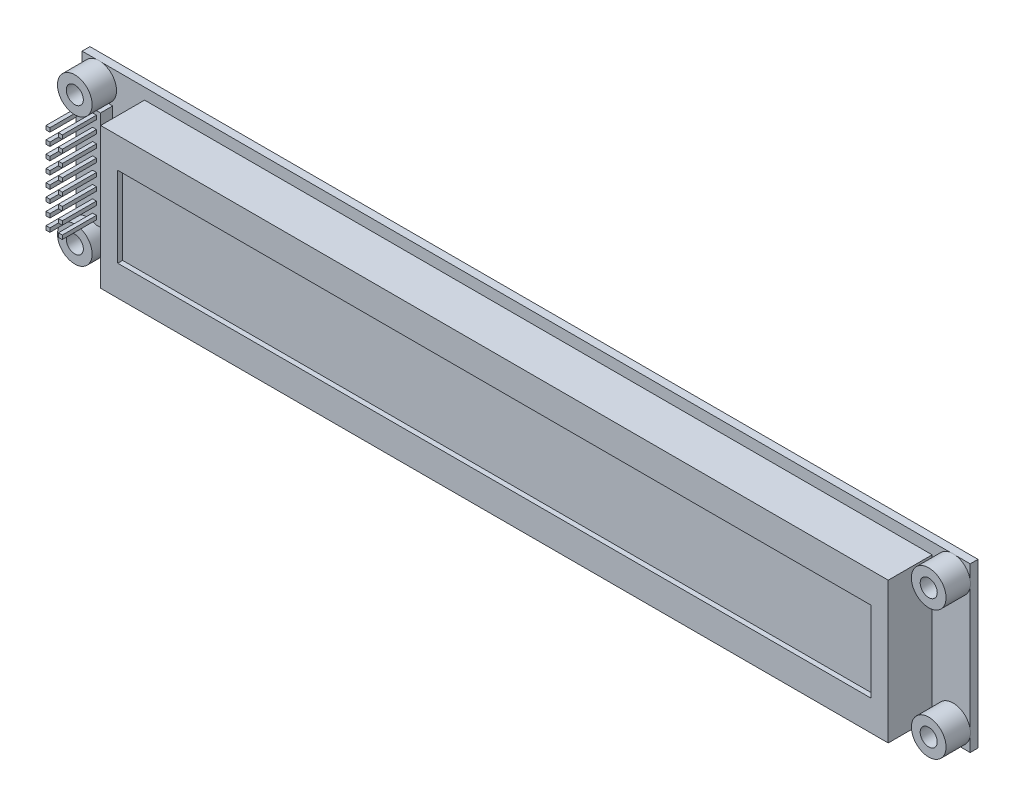
SolidWorks part; units mm, degrees
ref_plane "Спереди" through (0, 0, 0) normal (0, 0, 1) x (1, 0, 0)
ref_plane "Сверху" through (0, 0, 0) normal (0, 1, 0) x (1, 0, 0)
ref_plane "Справа" through (0, 0, 0) normal (1, 0, 0) x (0, 0, -1)
ref_plane "Плоскость4" through (0, 0, -6.6) normal (0, 0, 1) x (1, 0, 0)
sketch "Эскиз2" plane through (0, 0, -6.6) normal (0, 0, 1) x (1, 0, 0)
  line L1 (-91, -16.75) -> (91, -16.75)
  line L2 (-91, -16.75) -> (-91, 16.75)
  line L3 (-91, 16.75) -> (91, 16.75)
  line L4 (91, -16.75) -> (91, 16.75)
  line L5 (-91, -16.75) -> (91, 16.75) construction
  line L6 (-91, 16.75) -> (91, -16.75) construction
  point P0 (0, 0)
  dimension "D1" = 182
  dimension "D2" = 33.5
extrude "Бобышка-Вытянуть1" add sketch "Эскиз2" along normal blind 1.6
ref_plane "Плоскость5" through (0, 0, 0) normal (0, -1, 0) x (-1, 0, 0)
sketch "Эскиз3" plane through (0, 0, -5) normal (0, 0, 1) x (1, 0, 0)
  line L0 (-0.88, 0) -> (0.88, 0) construction
  line L1 (-78.2, 14.45) -> (83.2, 14.45)
  line L2 (-78.2, 14.45) -> (-78.2, -14.45)
  line L3 (-78.2, -14.45) -> (83.2, -14.45)
  line L4 (83.2, 14.45) -> (83.2, -14.45)
  line L5 (-78.2, 14.45) -> (83.2, -14.45) construction
  line L6 (-78.2, -14.45) -> (83.2, 14.45) construction
  line L7 (-91, 16.75) -> (-91, -16.75) construction
  point P0 (2.5, 0)
  dimension "D1" = 93.5
  dimension "D2" = 161.4
  dimension "D3" = 28.9
extrude "Бобышка-Вытянуть2" add sketch "Эскиз3" along normal blind 9
sketch "Эскиз4" plane through (0, 0, 4) normal (0, 0, 1) x (1, 0, 0)
  line L0 (-0.88, 0) -> (0.88, 0) construction
  line L1 (79.7, -8.25) -> (-74.7, -8.25)
  line L2 (79.7, -8.25) -> (79.7, 8.25)
  line L3 (79.7, 8.25) -> (-74.7, 8.25)
  line L4 (-74.7, -8.25) -> (-74.7, 8.25)
  line L5 (79.7, -8.25) -> (-74.7, 8.25) construction
  line L6 (79.7, 8.25) -> (-74.7, -8.25) construction
  line L7 (-91, 16.75) -> (-91, -16.75) construction
  point P0 (2.5, 0)
  dimension "D1" = 154.4
  dimension "D2" = 16.5
  dimension "D3" = 16.3
extrude "Вырез-Вытянуть1" cut sketch "Эскиз4" against normal blind 1
sketch "Эскиз5" plane through (0, 0, -5) normal (0, 0, 1) x (1, 0, 0)
  line L0 (-91, -16.75) -> (91, -16.75) construction
  line L1 (-91, 16.75) -> (-91, -16.75) construction
  circle A0 centre (-87.5, 13.25) radius 1.75
  circle A1 centre (-87.5, -13.25) radius 1.75
  circle A2 centre (87.5, -13.25) radius 1.75
  circle A3 centre (87.5, 13.25) radius 1.75
  dimension "D3" = 3.5
  dimension "D1" = 26.5
  dimension "D2" = 3.5
  dimension "D4" = 3.5
  dimension "D5" = 175
sketch "Эскиз6" plane through (0, 0, -5) normal (0, 0, -1) x (-1, 0, 0)
  circle A0 centre (-87.5, -13.25) radius 3.55
  circle A1 centre (-87.5, 13.25) radius 3.55
  circle A2 centre (87.5, 13.25) radius 3.55
  circle A3 centre (87.5, -13.25) radius 3.55
  dimension "D1" = 7.1
extrude "Бобышка-Вытянуть3" add sketch "Эскиз6" against normal blind 5
extrude "Вырез-Вытянуть2" cut sketch "Эскиз5" against normal through all both and the other way through all
sketch "Эскиз9" plane through (0, 0, -5) normal (0, 0, 1) x (1, 0, 0)
  line L0 (-0.88, 0) -> (0.88, 0) construction
  line L1 (-89.73, 10.16) -> (-84.73, 10.16)
  line L2 (-89.73, 10.16) -> (-89.73, -10.16)
  line L3 (-89.73, -10.16) -> (-84.73, -10.16)
  line L4 (-84.73, 10.16) -> (-84.73, -10.16)
  line L5 (-89.73, 10.16) -> (-84.73, -10.16) construction
  line L6 (-89.73, -10.16) -> (-84.73, 10.16) construction
  line L7 (-91, 12.6563) -> (-91, -12.6563) construction
  point P0 (-87.23, 0)
  point P5 (0, 0)
  point P11 (0, 0)
  dimension "D1" = 5
  dimension "D2" = 20.32
  dimension "D3" = 3.77
extrude "Бобышка-Вытянуть5" add sketch "Эскиз9" along normal blind 2.5
sketch "Эскиз10" plane through (0, 0, -2.5) normal (0, 0, 1) x (1, 0, 0)
  line L0 (-88.0937, 16.75) -> (-91, 16.75) construction
  line L1 (-88.9, 9.35) -> (-88.1, 9.35)
  line L2 (-88.9, 9.35) -> (-88.9, 8.55)
  line L3 (-88.9, 8.55) -> (-88.1, 8.55)
  line L4 (-88.1, 9.35) -> (-88.1, 8.55)
  line L5 (-88.9, 9.35) -> (-88.1, 8.55) construction
  line L6 (-88.9, 8.55) -> (-88.1, 9.35) construction
  point P0 (-88.5, 8.95)
  point P5 (0, 0)
  dimension "D1" = 0.8
  dimension "D2" = 0.8
  dimension "D3" = 1.27
  dimension "D4" = 7.8
extrude "Бобышка-Вытянуть6" add sketch "Эскиз10" along normal blind 7
pattern_linear "Линейный массив1" count 2 spacing 2.54 along (1, 0, 0) count 8 spacing 2.54 along (0, -1, 0) of "Бобышка-Вытянуть6"
